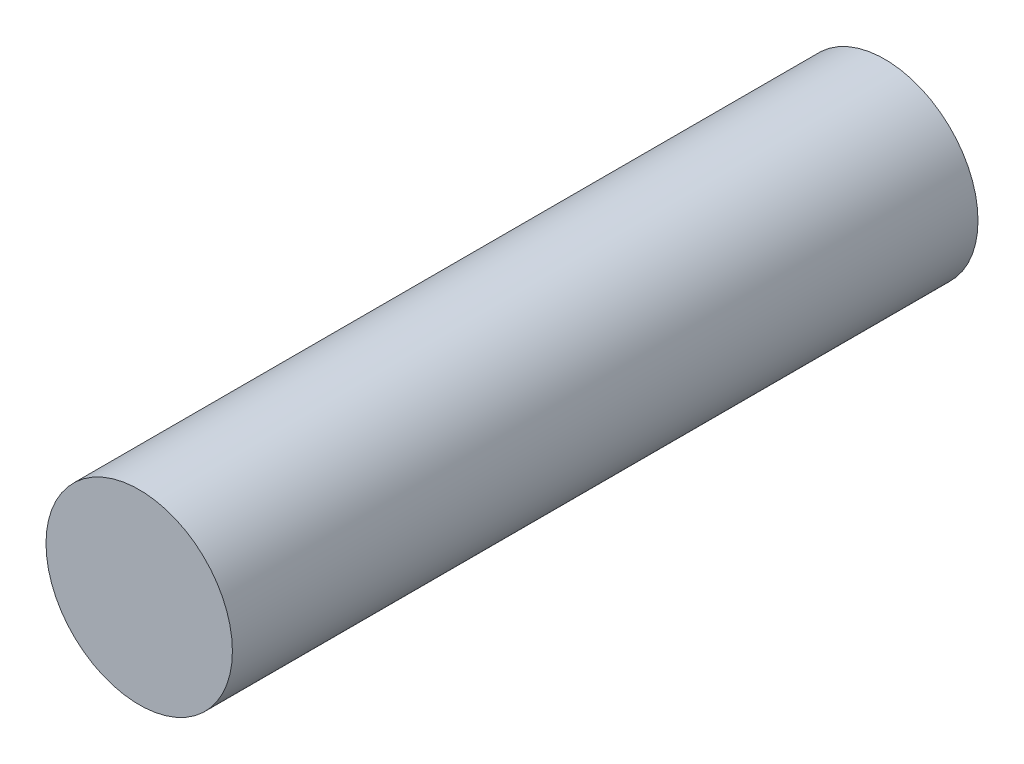
SolidWorks part; units mm, degrees
ref_plane "前视基准面" through (0, 0, 0) normal (0, 0, 1) x (1, 0, 0)
ref_plane "上视基准面" through (0, 0, 0) normal (0, 1, 0) x (1, 0, 0)
ref_plane "右视基准面" through (0, 0, 0) normal (1, 0, 0) x (0, 0, -1)
sketch "草图1" plane through (0, 0, 0) normal (0, 0, 1) x (1, 0, 0)
  circle A0 centre (0, 0) radius 1.5
extrude "凸台-拉伸1" add sketch "草图1" along normal blind 12
